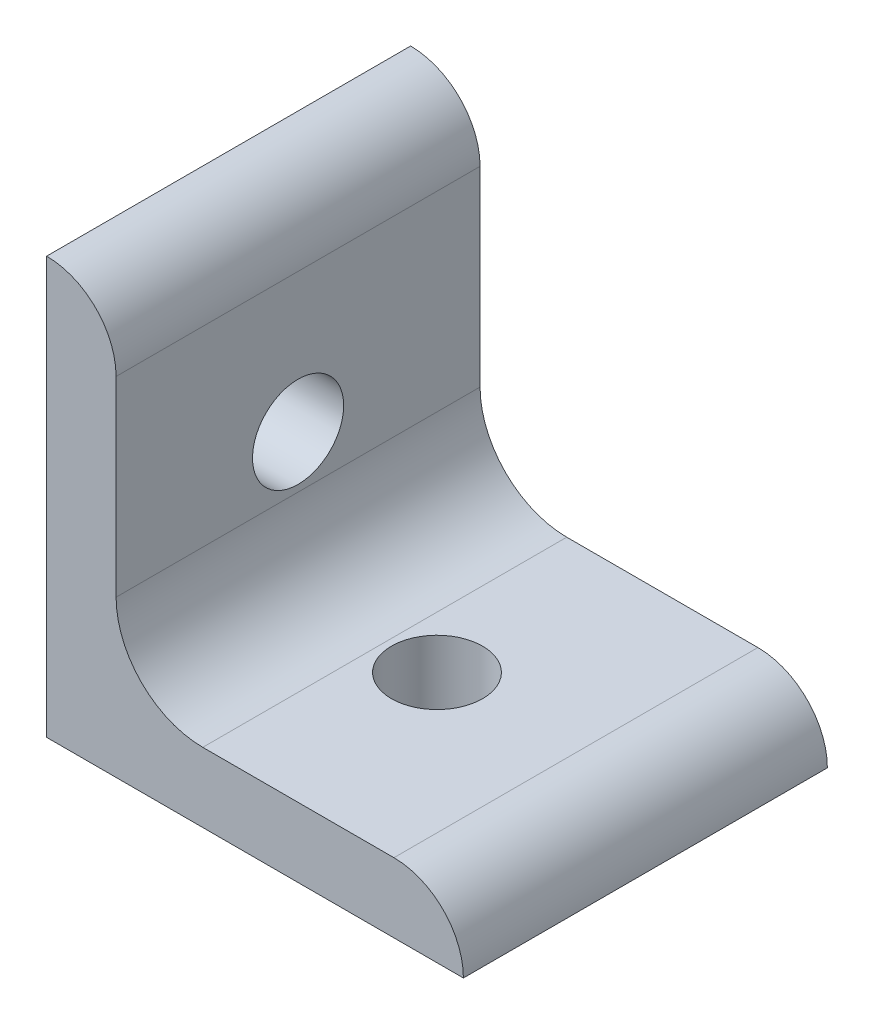
SolidWorks part; units mm, degrees
ref_plane "Front Plane" through (0, 0, 0) normal (0, 0, 1) x (1, 0, 0)
ref_plane "Top Plane" through (0, 0, 0) normal (0, 1, 0) x (1, 0, 0)
ref_plane "Right Plane" through (0, 0, 0) normal (1, 0, 0) x (0, 0, -1)
sketch "Sketch1" plane through (0, 0, 0) normal (0, 0, 1) x (1, 0, 0)
  line L0 (-19.05, -19.05) -> (-19.05, 19.05) construction
  line L1 (19.05, -19.05) -> (-19.05, -19.05) construction
  point P3 (-19.05, 0)
  point P6 (0, -19.05)
  dimension "For Rail Height" = 38.1
  dimension "Length" = 38.1
sketch "Sketch2" plane through (0, 0, 0) normal (1, 0, 0) x (0, 0, -1)
  line L0 (16.637, 0) -> (-16.637, 0) construction
  point P4 (0, 0)
  dimension "Thickness" = 33.274
sketch "Sketch3" plane through (0, 0, 0) normal (0, 0, 1) x (1, 0, 0)
  line L0 (-19.05, 19.05) -> (-19.05, -19.05)
  line L1 (-19.05, -19.05) -> (19.05, -19.05)
  line L2 (-12.7, 12.7) -> (-12.7, -4.7752)
  line L3 (-4.7752, -12.7) -> (12.7, -12.7)
  line L4 (19.05, -19.05) -> (-19.05, -19.05) construction
  arc A0 (12.7, -12.7) -> (19.05, -19.05) centre (12.7, -19.05) cw
  arc A1 (-12.7, 12.7) -> (-19.05, 19.05) centre (-19.05, 12.7) ccw
  arc A2 (-12.7, -4.7752) -> (-4.7752, -12.7) centre (-4.7752, -4.7752) ccw
  dimension "D1" = 6.35
  dimension "D2" = 7.9248
extrude "Boss-Extrude1" add sketch "Sketch3" along normal up to vertex (16.637 mm away) and the other way up to vertex (16.637 mm away) up to point (0, 0, 16.637) other way up to point (0, 0, -16.637)
sketch "Sketch4" plane through (0, 0, 0) normal (0, 1, 0) x (1, 0, 0)
  circle A0 centre (0, 0) radius 4.1656
  dimension "D1" = 8.3312
extrude "Cut-Extrude1" cut sketch "Sketch4" against normal through all both and the other way through all
sketch "Sketch5" plane through (0, 0, 0) normal (1, 0, 0) x (0, 0, -1)
  circle A0 centre (0, 0) radius 4.1656
  dimension "D1" = 8.3312
extrude "Cut-Extrude2" cut sketch "Sketch5" against normal through all both and the other way through all
equation "\"D1@Sketch5\"=\"d1@sketch4\""
